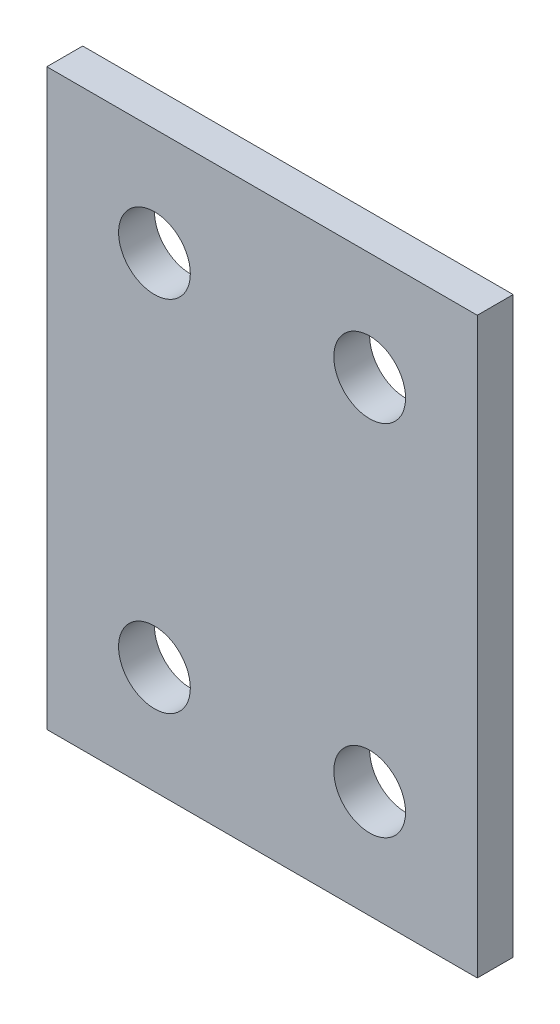
SolidWorks part; units mm, degrees
ref_plane "Front Plane" through (0, 0, 0) normal (0, 0, 1) x (1, 0, 0)
ref_plane "Top Plane" through (0, 0, 0) normal (0, 1, 0) x (1, 0, 0)
ref_plane "Right Plane" through (0, 0, 0) normal (1, 0, 0) x (0, 0, -1)
other "Configuration Table"
sketch "Sketch1" plane through (0, 0, 0) normal (0, 0, 1) x (1, 0, 0)
  line L1 (0, 0) -> (60, 0)
  line L2 (0, 0) -> (0, 80)
  line L3 (0, 80) -> (60, 80)
  line L4 (60, 0) -> (60, 80)
  circle A0 centre (15, 15) radius 5
  circle A1 centre (45, 15) radius 5
  circle A2 centre (15, 65) radius 5
  circle A3 centre (45, 65) radius 5
extrude "Extrude1" add sketch "Sketch1" against normal blind 5
